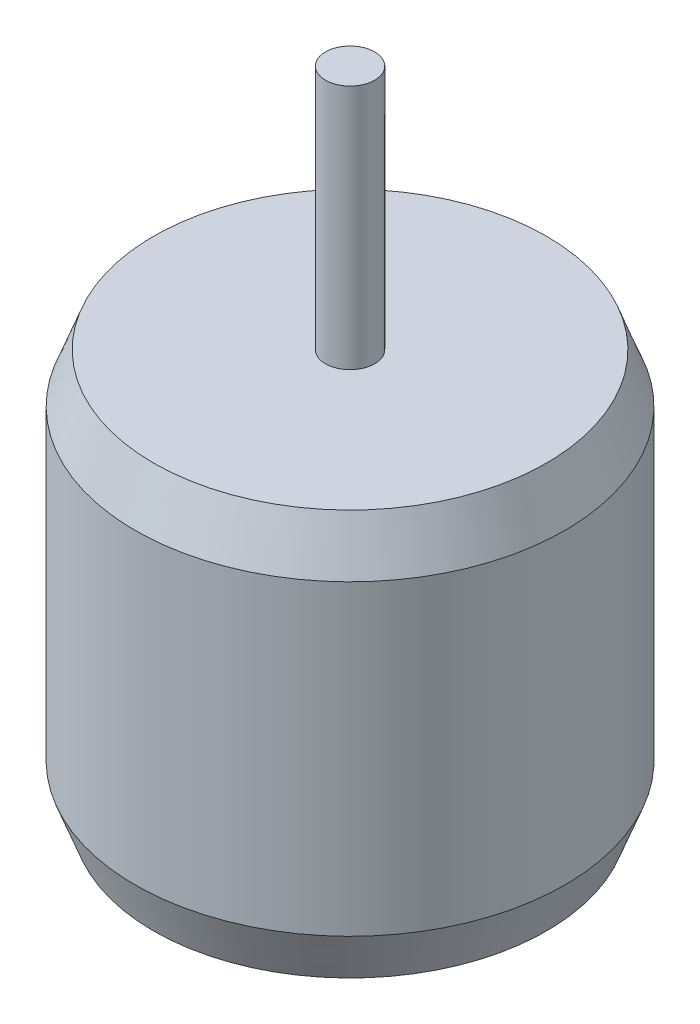
SolidWorks part; units mm, degrees
ref_plane "Front Plane" through (0, 0, 0) normal (0, 0, 1) x (1, 0, 0)
ref_plane "Top Plane" through (0, 0, 0) normal (0, 1, 0) x (1, 0, 0)
ref_plane "Right Plane" through (0, 0, 0) normal (1, 0, 0) x (0, 0, -1)
sketch "Sketch1" plane through (0, 0, 0) normal (1, 0, 0) x (0, 0, -1)
  line L0 (0, 0) -> (-2, 0)
  line L1 (-2, 0) -> (-2, -20)
  line L2 (-2, -20) -> (-16, -20)
  line L3 (-16, -20) -> (-17.5, -24)
  line L4 (-17.5, -24) -> (-17.5, -49)
  line L5 (-17.5, -49) -> (-16, -53)
  line L6 (-16, -53) -> (-6, -53)
  line L7 (-6, -53) -> (-6, -55)
  line L8 (-6, -55) -> (0, -55)
  line L9 (0, -55) -> (0, 0)
  dimension "D1" = 17.5
  dimension "D2" = 20
  dimension "D3" = 2
  dimension "D4" = 35
  dimension "D5" = 2
  dimension "D6" = 25
  dimension "D7" = 1.5
  dimension "D8" = 6
revolve "Revolve1" add sketch "Sketch1" angle 360 about L9
